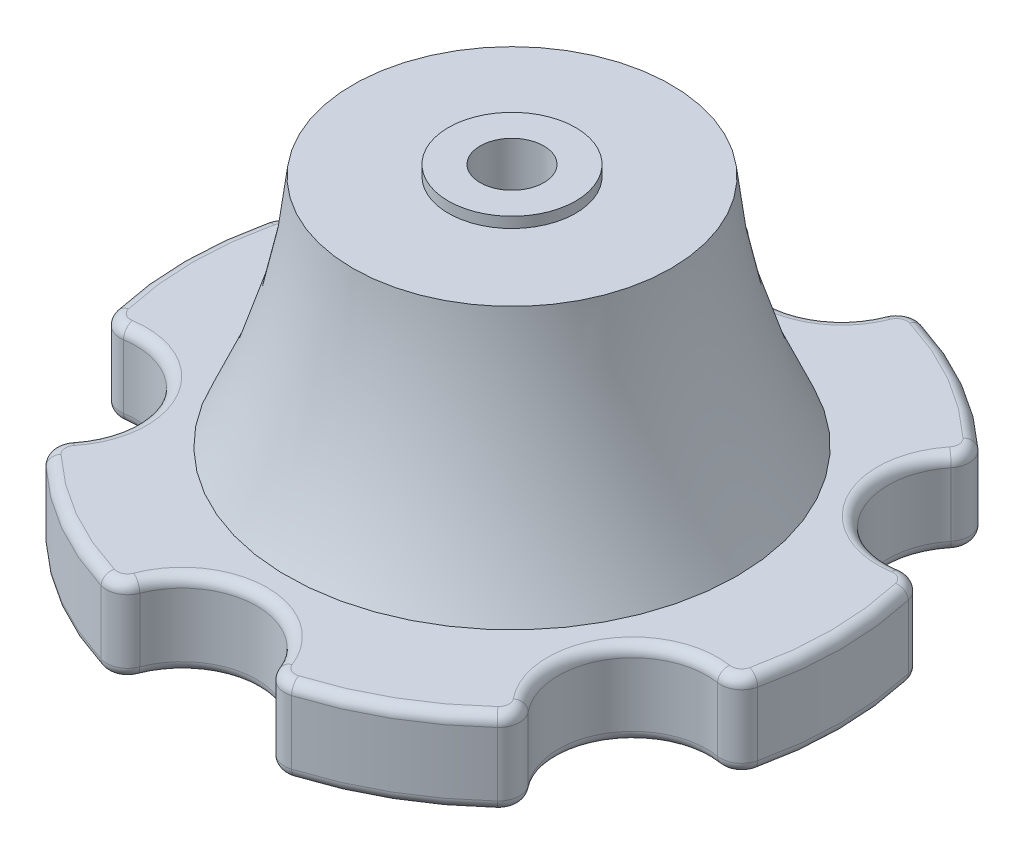
SolidWorks part; units mm, degrees
ref_plane "Спереди" through (0, 0, 0) normal (0, 0, 1) x (1, 0, 0)
ref_plane "Сверху" through (0, 0, 0) normal (0, 1, 0) x (1, 0, 0)
ref_plane "Справа" through (0, 0, 0) normal (1, 0, 0) x (0, 0, -1)
sketch "Эскиз1" plane through (0, 0, 0) normal (0, 1, 0) x (1, 0, 0)
  circle A0 centre (0, 0) radius 15.53 construction
  arc A1 (-3.4777, 15.1356) -> (3.4777, 15.1356) centre (0, 15.53) ccw
  arc A2 (3.4777, 15.1356) -> (11.369, 10.5796) centre (0, 0) cw
  arc A3 (11.369, 10.5796) -> (14.8467, 4.556) centre (13.4494, 7.765) ccw
  arc A4 (14.8467, 4.556) -> (14.8467, -4.556) centre (0, 0) cw
  arc A5 (14.8467, -4.556) -> (11.369, -10.5796) centre (13.4494, -7.765) ccw
  arc A6 (11.369, -10.5796) -> (3.4777, -15.1356) centre (0, 0) cw
  arc A7 (3.4777, -15.1356) -> (-3.4777, -15.1356) centre (0, -15.53) ccw
  arc A8 (-3.4777, -15.1356) -> (-11.369, -10.5796) centre (0, 0) cw
  arc A9 (-11.369, -10.5796) -> (-14.8467, -4.556) centre (-13.4494, -7.765) ccw
  arc A10 (-14.8467, -4.556) -> (-14.8467, 4.556) centre (0, 0) cw
  arc A11 (-14.8467, 4.556) -> (-11.369, 10.5796) centre (-13.4494, 7.765) ccw
  arc A12 (-11.369, 10.5796) -> (-3.4777, 15.1356) centre (0, 0) cw
  point P30 (0, 0)
  dimension "D1" = 3.5
  dimension "D3" = 6
  dimension "D2" = 15.53
extrude "Бобышка-Вытянуть1" add sketch "Эскиз1" along normal blind 15
sketch "Эскиз2" plane through (0, 0, 0) normal (0, 0, 1) x (1, 0, 0)
  line L0 (0, -1000) -> (0, 49000) construction
  line L1 (-15.6, 31) -> (-15.6, 4)
  line L2 (-15.6, 31) -> (-10.6, 31)
  line L3 (-15.6, 4) -> (-10.6, 4)
  line L4 (-3.4777, 0) -> (3.4777, 0) construction
  arc A0 (-10.6, 31) -> (-10.6, 4) centre (-37.3909, 17.5) cw
  dimension "D4" = 30
  dimension "D1" = 15.6
  dimension "D2" = 27
  dimension "D3" = 5
  dimension "D5" = 4
revolve "Вырез-Повернуть1" cut sketch "Эскиз2" angle 360 about L0
sketch "Эскиз3" plane through (0, 0, 0) normal (0, -1, 0) x (1, 0, 0)
  circle A0 centre (0, 0) radius 1.5
  dimension "D1" = 3
extrude "Вырез-Вытянуть1" cut sketch "Эскиз3" against normal blind 15
sketch "Эскиз4" plane through (0, 0, 0) normal (0, -1, 0) x (1, 0, 0)
  circle A0 centre (0, 0) radius 3
  dimension "D1" = 6
extrude "Вырез-Вытянуть2" cut sketch "Эскиз4" against normal blind 6
fillet "Скругление1" radius 1 12 edges at (-11.369, 2, 10.5796) (-3.4777, 2, 15.1356) (3.4777, 2, 15.1356) (11.369, 2, 10.5796) (14.8467, 2, 4.556) (14.8467, 2, -4.556) (11.369, 2, -10.5796) (-3.4777, 2, -15.1356) (3.4777, 2, -15.1356) (-11.369, 2, -10.5796) (-14.8467, 2, -4.556) (-14.8467, 2, 4.556)
fillet "Скругление2" radius 0.5 48 edges at (3.7592, 4, 14.8086) (0, 4, 12.03) (-3.7592, 4, 14.8086) (-7.765, 4, 13.4494) (-10.9451, 4, 10.6598) (-10.4183, 4, 6.015) (-14.7042, 4, 4.1488) (-15.53, 4, 0) (-14.7042, 4, -4.1488) (-10.4183, 4, -6.015) (-10.9451, 4, -10.6598) (-7.765, 4, -13.4494) (-3.7592, 4, -14.8086) (0, 4, -12.03) (3.7592, 4, -14.8086) (7.765, 4, -13.4494) (10.9451, 4, -10.6598) (10.4183, 4, -6.015) (14.7042, 4, -4.1488) (15.53, 4, 0) (14.7042, 4, 4.1488) (10.4183, 4, 6.015) (10.9451, 4, 10.6598) (-10.9451, 0, 10.6598) (-10.4183, 0, 6.015) (-14.7042, 0, 4.1488) (-15.53, 0, 0) (-14.7042, 0, -4.1488) (-10.4183, 0, -6.015) (-10.9451, 0, -10.6598) (-7.765, 0, -13.4494) (-3.7592, 0, -14.8086) (0, 0, -12.03) (3.7592, 0, -14.8086) (7.765, 0, -13.4494) (10.9451, 0, -10.6598) (10.4183, 0, -6.015) (14.7042, 0, -4.1488) (15.53, 0, 0) (14.7042, 0, 4.1488) (10.4183, 0, 6.015) (10.9451, 0, 10.6598) (7.765, 0, 13.4494) (3.7592, 0, 14.8086) (0, 0, 12.03) (-3.7592, 0, 14.8086) (7.765, 4, 13.4494) (-7.765, 0, 13.4494)
sketch "Эскиз5" plane through (0, 15, 0) normal (0, 1, 0) x (1, 0, 0)
  circle A0 centre (0, 0) radius 3
  circle A1 centre (0, 0) radius 1.5
  circle A3 centre (0, 0) radius 1.5 construction
  dimension "D1" = 6
extrude "Бобышка-Вытянуть2" add sketch "Эскиз5" along normal blind 0.5
